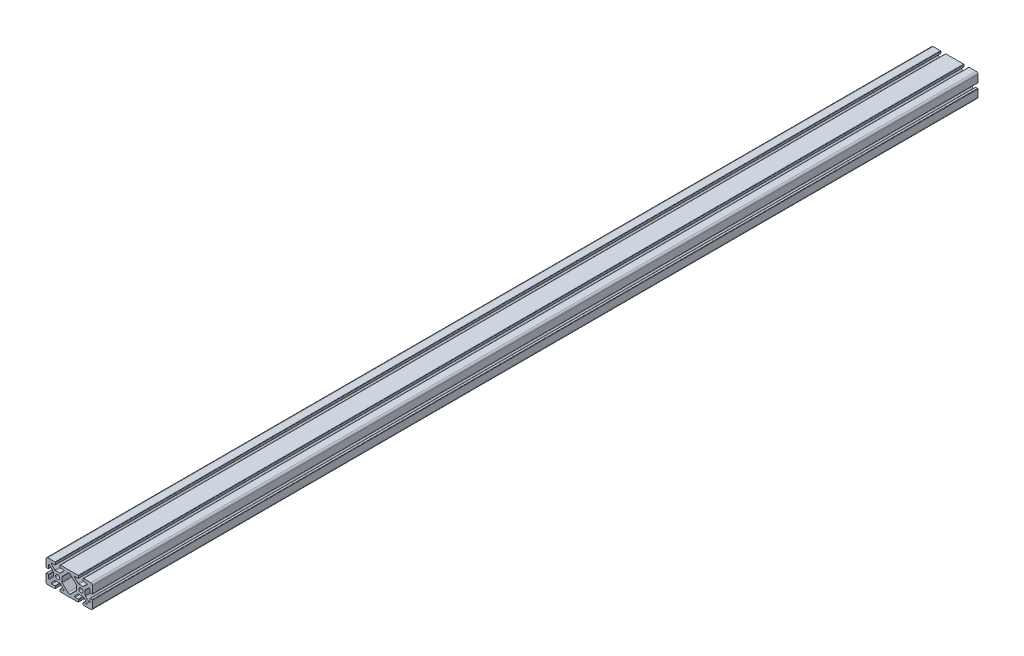
SolidWorks part; units mm, degrees
ref_plane "Front Plane" through (0, 0, 0) normal (0, 0, 1) x (1, 0, 0)
ref_plane "Top Plane" through (0, 0, 0) normal (0, 1, 0) x (1, 0, 0)
ref_plane "Right Plane" through (0, 0, 0) normal (1, 0, 0) x (0, 0, -1)
sketch "Sketch1" plane through (0, 0, 0) normal (0, 0, 1) x (1, 0, 0)
  line L0 (-40, 17) -> (-40, 4.75)
  line L1 (-37, 20) -> (-24.75, 20)
  line L2 (-24, 19.25) -> (-24, 16.25)
  line L3 (-24.75, 15.5) -> (-30.068, 15.5)
  line L4 (-30.727, 13.909) -> (-24.8599, 8.0419)
  line L5 (-33.909, 10.727) -> (-28.0419, 4.8599)
  line L6 (-35.5, 10.068) -> (-35.5, 4.75)
  line L7 (-36.25, 4) -> (-39.25, 4)
  line L8 (-23.5517, 7.5) -> (-16.4483, 7.5)
  line L9 (-27.5, 3.5517) -> (-27.5, -3.5517)
  line L10 (0, 20) -> (-15.25, 20)
  line L11 (-16, 19.25) -> (-16, 16.25)
  line L12 (-15.25, 15.5) -> (-9.932, 15.5)
  line L13 (-12.5, 3.5517) -> (-12.5, -3.5517)
  line L14 (-9.273, 13.909) -> (-15.1401, 8.0419)
  line L15 (-2.25, 14.568) -> (-11.9581, 4.8599)
  line L16 (-36.25, -4) -> (-39.25, -4)
  line L17 (-35.5, -10.068) -> (-35.5, -4.75)
  line L18 (-33.909, -10.727) -> (-28.0419, -4.8599)
  line L19 (-30.727, -13.909) -> (-24.8599, -8.0419)
  line L20 (-24.75, -15.5) -> (-30.068, -15.5)
  line L21 (-24, -19.25) -> (-24, -16.25)
  line L22 (-37, -20) -> (-24.75, -20)
  line L23 (-40, -17) -> (-40, -4.75)
  line L24 (0, -20) -> (-15.25, -20)
  line L25 (-16, -19.25) -> (-16, -16.25)
  line L26 (-15.25, -15.5) -> (-9.932, -15.5)
  line L27 (-9.273, -13.909) -> (-15.1401, -8.0419)
  line L28 (-2.25, -14.568) -> (-11.9581, -4.8599)
  line L29 (-23.5517, -7.5) -> (-16.4483, -7.5)
  line L58 (0, 20) -> (0, -20) construction
  line L59 (-12.5, 0) -> (0, 0) construction
  line L60 (0, 15.5) -> (15.25, 15.5) construction
  line L61 (0, -15.5) -> (15.25, -15.5) construction
  line L62 (-24, 17.75) -> (-16, 17.75) construction
  line L63 (-20, 17.75) -> (-20, 0) construction
  line L64 (-37.75, 4) -> (-37.75, -4) construction
  circle A0 centre (-20, 0) radius 3.5
  arc A1 (-40, 17) -> (-37, 20) centre (-37, 17) cw
  arc A2 (-33.909, 10.727) -> (-35.5, 10.068) centre (-34.568, 10.068) ccw
  arc A3 (-30.068, 15.5) -> (-30.727, 13.909) centre (-30.068, 14.568) ccw
  arc A4 (-24.75, 20) -> (-24, 19.25) centre (-24.75, 19.25) cw
  arc A5 (-40, 4.75) -> (-39.25, 4) centre (-39.25, 4.75) ccw
  arc A6 (-35.5, 4.75) -> (-36.25, 4) centre (-36.25, 4.75) cw
  arc A7 (-24, 16.25) -> (-24.75, 15.5) centre (-24.75, 16.25) cw
  arc A8 (-23.5517, 7.5) -> (-24.8599, 8.0419) centre (-23.5517, 9.35) cw
  arc A9 (-27.5, 3.5517) -> (-28.0419, 4.8599) centre (-29.35, 3.5517) ccw
  arc A10 (0, 15.5) -> (-2.25, 14.568) centre (0, 12.318) ccw
  arc A11 (-2.25, -14.568) -> (0, -15.5) centre (0, -12.318) ccw
  arc A12 (-15.25, 20) -> (-16, 19.25) centre (-15.25, 19.25) ccw
  arc A13 (-16, 16.25) -> (-15.25, 15.5) centre (-15.25, 16.25) ccw
  arc A14 (-16.4483, 7.5) -> (-15.1401, 8.0419) centre (-16.4483, 9.35) ccw
  arc A15 (-12.5, 3.5517) -> (-11.9581, 4.8599) centre (-10.65, 3.5517) cw
  arc A16 (-9.932, 15.5) -> (-9.273, 13.909) centre (-9.932, 14.568) cw
  arc A17 (-27.5, -3.5517) -> (-28.0419, -4.8599) centre (-29.35, -3.5517) cw
  arc A18 (-23.5517, -7.5) -> (-24.8599, -8.0419) centre (-23.5517, -9.35) ccw
  arc A19 (-24, -16.25) -> (-24.75, -15.5) centre (-24.75, -16.25) ccw
  arc A20 (-35.5, -4.75) -> (-36.25, -4) centre (-36.25, -4.75) ccw
  arc A21 (-40, -4.75) -> (-39.25, -4) centre (-39.25, -4.75) cw
  arc A22 (-24.75, -20) -> (-24, -19.25) centre (-24.75, -19.25) ccw
  arc A23 (-30.068, -15.5) -> (-30.727, -13.909) centre (-30.068, -14.568) cw
  arc A24 (-33.909, -10.727) -> (-35.5, -10.068) centre (-34.568, -10.068) cw
  arc A25 (-40, -17) -> (-37, -20) centre (-37, -17) ccw
  arc A26 (-9.932, -15.5) -> (-9.273, -13.909) centre (-9.932, -14.568) ccw
  arc A27 (-15.25, -20) -> (-16, -19.25) centre (-15.25, -19.25) cw
  arc A28 (-16, -16.25) -> (-15.25, -15.5) centre (-15.25, -16.25) cw
  arc A29 (-16.4483, -7.5) -> (-15.1401, -8.0419) centre (-16.4483, -9.35) cw
  arc A30 (-12.5, -3.5517) -> (-11.9581, -4.8599) centre (-10.65, -3.5517) ccw
  point P36 (-27.5, 0)
  point P98 (-37.75, 0)
  point P103 (-20, 7.5)
  point P105 (-20, -7.5)
  dimension "D7" = 7
  dimension "D9" = 3
  dimension "D17" = 0.75
  dimension "D23" = 1.85
  dimension "Rail Width" = 40
  dimension "Rail Height" = 80
  dimension "D3" = 40
  dimension "D4" = 20
  dimension "D6" = 4.5
  dimension "D8" = 4.5
  dimension "D10" = 4.5
  dimension "D11" = 4.5
  dimension "Slot Width" = 8
  dimension "D13" = 45
  dimension "D14" = 45
  dimension "D15" = 4.5
  dimension "D16" = 8
  dimension "D19" = 8
  dimension "D20" = 7.5
  dimension "D21" = 8
  dimension "D22" = 7.5
  dimension "D5" = 22
  dimension "D18" = 22
sketch "Sketch2" plane through (0, 0, 0) normal (1, 0, 0) x (0, 0, -1)
  line L0 (-762, -20) -> (762, -20)
  point P2 (-723.9, -20)
  point P3 (723.9, -20)
  dimension "Length" = 1524
  dimension "D1" = 38.1
  dimension "D2" = 38.1
sketch "Sketch3" plane through (0, 0, 0) normal (0, 0, 1) x (1, 0, 0)
  line L0 (0, 20) -> (-15.25, 20) construction
  line L1 (-16, 19.25) -> (-16, 16.25) construction
  line L2 (-15.25, 15.5) -> (-9.932, 15.5) construction
  line L3 (-9.273, 13.909) -> (-15.1401, 8.0419) construction
  line L4 (-23.5517, 7.5) -> (-16.4483, 7.5) construction
  line L5 (-30.727, 13.909) -> (-24.8599, 8.0419) construction
  line L6 (-24.75, 15.5) -> (-30.068, 15.5) construction
  line L7 (-24, 19.25) -> (-24, 16.25) construction
  line L8 (-37, 20) -> (-24.75, 20) construction
  line L9 (-40, 17) -> (-40, 4.75) construction
  line L10 (-36.25, 4) -> (-39.25, 4) construction
  line L11 (-35.5, 10.068) -> (-35.5, 4.75) construction
  line L12 (-33.909, 10.727) -> (-28.0419, 4.8599) construction
  line L13 (-27.5, 3.5517) -> (-27.5, -3.5517) construction
  line L14 (-33.909, -10.727) -> (-28.0419, -4.8599) construction
  line L15 (-35.5, -10.068) -> (-35.5, -4.75) construction
  line L16 (-36.25, -4) -> (-39.25, -4) construction
  line L17 (-40, -17) -> (-40, -4.75) construction
  line L18 (-37, -20) -> (-24.75, -20) construction
  line L19 (-24, -19.25) -> (-24, -16.25) construction
  line L20 (-24.75, -15.5) -> (-30.068, -15.5) construction
  line L21 (-30.727, -13.909) -> (-24.8599, -8.0419) construction
  line L22 (-23.5517, -7.5) -> (-16.4483, -7.5) construction
  line L23 (-9.273, -13.909) -> (-15.1401, -8.0419) construction
  line L24 (-15.25, -15.5) -> (-9.932, -15.5) construction
  line L25 (-16, -19.25) -> (-16, -16.25) construction
  line L26 (0, -20) -> (-15.25, -20) construction
  line L27 (-2.25, -14.568) -> (-11.9581, -4.8599) construction
  line L28 (-12.5, 3.5517) -> (-12.5, -3.5517) construction
  line L29 (-2.25, 14.568) -> (-11.9581, 4.8599) construction
  line L30 (15.25, 20) -> (-15.25, 20)
  line L31 (-16, 19.25) -> (-16, 16.25)
  line L32 (-15.25, 15.5) -> (-9.932, 15.5)
  line L33 (-9.273, 13.909) -> (-15.1401, 8.0419)
  line L34 (-23.5517, 7.5) -> (-16.4483, 7.5)
  line L35 (-30.727, 13.909) -> (-24.8599, 8.0419)
  line L36 (-24.75, 15.5) -> (-30.068, 15.5)
  line L37 (-24, 19.25) -> (-24, 16.25)
  line L38 (-37, 20) -> (-24.75, 20)
  line L39 (-40, 17) -> (-40, 4.75)
  line L40 (-36.25, 4) -> (-39.25, 4)
  line L41 (-35.5, 10.068) -> (-35.5, 4.75)
  line L42 (-33.909, 10.727) -> (-28.0419, 4.8599)
  line L43 (-27.5, 3.5517) -> (-27.5, -3.5517)
  line L44 (-33.909, -10.727) -> (-28.0419, -4.8599)
  line L45 (-35.5, -10.068) -> (-35.5, -4.75)
  line L46 (-36.25, -4) -> (-39.25, -4)
  line L47 (-40, -17) -> (-40, -4.75)
  line L48 (-37, -20) -> (-24.75, -20)
  line L49 (-24, -19.25) -> (-24, -16.25)
  line L50 (-24.75, -15.5) -> (-30.068, -15.5)
  line L51 (-30.727, -13.909) -> (-24.8599, -8.0419)
  line L52 (-23.5517, -7.5) -> (-16.4483, -7.5)
  line L53 (-9.273, -13.909) -> (-15.1401, -8.0419)
  line L54 (-15.25, -15.5) -> (-9.932, -15.5)
  line L55 (-16, -19.25) -> (-16, -16.25)
  line L56 (15.25, -20) -> (-15.25, -20)
  line L57 (-2.25, -14.568) -> (-11.9581, -4.8599)
  line L58 (-12.5, 3.5517) -> (-12.5, -3.5517)
  line L59 (-2.25, 14.568) -> (-11.9581, 4.8599)
  line L60 (0, 20) -> (0, -20) construction
  line L61 (2.25, 14.568) -> (11.9581, 4.8599)
  line L62 (12.5, 3.5517) -> (12.5, -3.5517)
  line L63 (2.25, -14.568) -> (11.9581, -4.8599)
  line L64 (16, 19.25) -> (16, 16.25)
  line L65 (15.25, 15.5) -> (9.932, 15.5)
  line L66 (9.273, 13.909) -> (15.1401, 8.0419)
  line L67 (23.5517, 7.5) -> (16.4483, 7.5)
  line L68 (30.727, 13.909) -> (24.8599, 8.0419)
  line L69 (24.75, 15.5) -> (30.068, 15.5)
  line L70 (24, 19.25) -> (24, 16.25)
  line L71 (37, 20) -> (24.75, 20)
  line L72 (40, 17) -> (40, 4.75)
  line L73 (36.25, 4) -> (39.25, 4)
  line L74 (35.5, 10.068) -> (35.5, 4.75)
  line L75 (33.909, 10.727) -> (28.0419, 4.8599)
  line L76 (27.5, 3.5517) -> (27.5, -3.5517)
  line L77 (33.909, -10.727) -> (28.0419, -4.8599)
  line L78 (35.5, -10.068) -> (35.5, -4.75)
  line L79 (36.25, -4) -> (39.25, -4)
  line L80 (40, -17) -> (40, -4.75)
  line L81 (37, -20) -> (24.75, -20)
  line L82 (24, -19.25) -> (24, -16.25)
  line L83 (24.75, -15.5) -> (30.068, -15.5)
  line L84 (30.727, -13.909) -> (24.8599, -8.0419)
  line L85 (23.5517, -7.5) -> (16.4483, -7.5)
  line L86 (9.273, -13.909) -> (15.1401, -8.0419)
  line L87 (15.25, -15.5) -> (9.932, -15.5)
  line L88 (16, -19.25) -> (16, -16.25)
  circle A0 centre (-20, 0) radius 3.5 construction
  arc A1 (-15.25, 20) -> (-16, 19.25) centre (-15.25, 19.25) ccw construction
  arc A2 (-16, 16.25) -> (-15.25, 15.5) centre (-15.25, 16.25) ccw construction
  arc A3 (-9.273, 13.909) -> (-9.932, 15.5) centre (-9.932, 14.568) ccw construction
  arc A4 (-16.4483, 7.5) -> (-15.1401, 8.0419) centre (-16.4483, 9.35) ccw construction
  arc A5 (-24.8599, 8.0419) -> (-23.5517, 7.5) centre (-23.5517, 9.35) ccw construction
  arc A6 (-30.068, 15.5) -> (-30.727, 13.909) centre (-30.068, 14.568) ccw construction
  arc A7 (-24.75, 15.5) -> (-24, 16.25) centre (-24.75, 16.25) ccw construction
  arc A8 (-24, 19.25) -> (-24.75, 20) centre (-24.75, 19.25) ccw construction
  arc A9 (-37, 20) -> (-40, 17) centre (-37, 17) ccw construction
  arc A10 (-40, 4.75) -> (-39.25, 4) centre (-39.25, 4.75) ccw construction
  arc A11 (-36.25, 4) -> (-35.5, 4.75) centre (-36.25, 4.75) ccw construction
  arc A12 (-33.909, 10.727) -> (-35.5, 10.068) centre (-34.568, 10.068) ccw construction
  arc A13 (-27.5, 3.5517) -> (-28.0419, 4.8599) centre (-29.35, 3.5517) ccw construction
  arc A14 (-28.0419, -4.8599) -> (-27.5, -3.5517) centre (-29.35, -3.5517) ccw construction
  arc A15 (-35.5, -10.068) -> (-33.909, -10.727) centre (-34.568, -10.068) ccw construction
  arc A16 (-35.5, -4.75) -> (-36.25, -4) centre (-36.25, -4.75) ccw construction
  arc A17 (-39.25, -4) -> (-40, -4.75) centre (-39.25, -4.75) ccw construction
  arc A18 (-40, -17) -> (-37, -20) centre (-37, -17) ccw construction
  arc A19 (-24.75, -20) -> (-24, -19.25) centre (-24.75, -19.25) ccw construction
  arc A20 (-24, -16.25) -> (-24.75, -15.5) centre (-24.75, -16.25) ccw construction
  arc A21 (-30.727, -13.909) -> (-30.068, -15.5) centre (-30.068, -14.568) ccw construction
  arc A22 (-23.5517, -7.5) -> (-24.8599, -8.0419) centre (-23.5517, -9.35) ccw construction
  arc A23 (-15.1401, -8.0419) -> (-16.4483, -7.5) centre (-16.4483, -9.35) ccw construction
  arc A24 (-9.932, -15.5) -> (-9.273, -13.909) centre (-9.932, -14.568) ccw construction
  arc A25 (-15.25, -15.5) -> (-16, -16.25) centre (-15.25, -16.25) ccw construction
  arc A26 (-16, -19.25) -> (-15.25, -20) centre (-15.25, -19.25) ccw construction
  arc A27 (-2.25, -14.568) -> (0, -15.5) centre (0, -12.318) ccw construction
  arc A28 (-12.5, -3.5517) -> (-11.9581, -4.8599) centre (-10.65, -3.5517) ccw construction
  arc A29 (-11.9581, 4.8599) -> (-12.5, 3.5517) centre (-10.65, 3.5517) ccw construction
  arc A30 (0, 15.5) -> (-2.25, 14.568) centre (0, 12.318) ccw construction
  circle A31 centre (-20, 0) radius 3.5
  arc A32 (-15.25, 20) -> (-16, 19.25) centre (-15.25, 19.25) ccw
  arc A33 (-16, 16.25) -> (-15.25, 15.5) centre (-15.25, 16.25) ccw
  arc A34 (-9.273, 13.909) -> (-9.932, 15.5) centre (-9.932, 14.568) ccw
  arc A35 (-16.4483, 7.5) -> (-15.1401, 8.0419) centre (-16.4483, 9.35) ccw
  arc A36 (-24.8599, 8.0419) -> (-23.5517, 7.5) centre (-23.5517, 9.35) ccw
  arc A37 (-30.068, 15.5) -> (-30.727, 13.909) centre (-30.068, 14.568) ccw
  arc A38 (-24.75, 15.5) -> (-24, 16.25) centre (-24.75, 16.25) ccw
  arc A39 (-24, 19.25) -> (-24.75, 20) centre (-24.75, 19.25) ccw
  arc A40 (-37, 20) -> (-40, 17) centre (-37, 17) ccw
  arc A41 (-40, 4.75) -> (-39.25, 4) centre (-39.25, 4.75) ccw
  arc A42 (-36.25, 4) -> (-35.5, 4.75) centre (-36.25, 4.75) ccw
  arc A43 (-33.909, 10.727) -> (-35.5, 10.068) centre (-34.568, 10.068) ccw
  arc A44 (-27.5, 3.5517) -> (-28.0419, 4.8599) centre (-29.35, 3.5517) ccw
  arc A45 (-28.0419, -4.8599) -> (-27.5, -3.5517) centre (-29.35, -3.5517) ccw
  arc A46 (-35.5, -10.068) -> (-33.909, -10.727) centre (-34.568, -10.068) ccw
  arc A47 (-35.5, -4.75) -> (-36.25, -4) centre (-36.25, -4.75) ccw
  arc A48 (-39.25, -4) -> (-40, -4.75) centre (-39.25, -4.75) ccw
  arc A49 (-40, -17) -> (-37, -20) centre (-37, -17) ccw
  arc A50 (-24.75, -20) -> (-24, -19.25) centre (-24.75, -19.25) ccw
  arc A51 (-24, -16.25) -> (-24.75, -15.5) centre (-24.75, -16.25) ccw
  arc A52 (-30.727, -13.909) -> (-30.068, -15.5) centre (-30.068, -14.568) ccw
  arc A53 (-23.5517, -7.5) -> (-24.8599, -8.0419) centre (-23.5517, -9.35) ccw
  arc A54 (-15.1401, -8.0419) -> (-16.4483, -7.5) centre (-16.4483, -9.35) ccw
  arc A55 (-9.932, -15.5) -> (-9.273, -13.909) centre (-9.932, -14.568) ccw
  arc A56 (-15.25, -15.5) -> (-16, -16.25) centre (-15.25, -16.25) ccw
  arc A57 (-16, -19.25) -> (-15.25, -20) centre (-15.25, -19.25) ccw
  arc A58 (-2.25, -14.568) -> (2.25, -14.568) centre (0, -12.318) ccw
  arc A59 (-12.5, -3.5517) -> (-11.9581, -4.8599) centre (-10.65, -3.5517) ccw
  arc A60 (-11.9581, 4.8599) -> (-12.5, 3.5517) centre (-10.65, 3.5517) ccw
  arc A61 (2.25, 14.568) -> (-2.25, 14.568) centre (0, 12.318) ccw
  circle A62 centre (20, 0) radius 3.5
  arc A63 (11.9581, 4.8599) -> (12.5, 3.5517) centre (10.65, 3.5517) cw
  arc A64 (12.5, -3.5517) -> (11.9581, -4.8599) centre (10.65, -3.5517) cw
  arc A65 (15.25, 20) -> (16, 19.25) centre (15.25, 19.25) cw
  arc A66 (16, 16.25) -> (15.25, 15.5) centre (15.25, 16.25) cw
  arc A67 (9.273, 13.909) -> (9.932, 15.5) centre (9.932, 14.568) cw
  arc A68 (16.4483, 7.5) -> (15.1401, 8.0419) centre (16.4483, 9.35) cw
  arc A69 (24.8599, 8.0419) -> (23.5517, 7.5) centre (23.5517, 9.35) cw
  arc A70 (30.068, 15.5) -> (30.727, 13.909) centre (30.068, 14.568) cw
  arc A71 (24.75, 15.5) -> (24, 16.25) centre (24.75, 16.25) cw
  arc A72 (24, 19.25) -> (24.75, 20) centre (24.75, 19.25) cw
  arc A73 (37, 20) -> (40, 17) centre (37, 17) cw
  arc A74 (40, 4.75) -> (39.25, 4) centre (39.25, 4.75) cw
  arc A75 (36.25, 4) -> (35.5, 4.75) centre (36.25, 4.75) cw
  arc A76 (33.909, 10.727) -> (35.5, 10.068) centre (34.568, 10.068) cw
  arc A77 (27.5, 3.5517) -> (28.0419, 4.8599) centre (29.35, 3.5517) cw
  arc A78 (28.0419, -4.8599) -> (27.5, -3.5517) centre (29.35, -3.5517) cw
  arc A79 (35.5, -10.068) -> (33.909, -10.727) centre (34.568, -10.068) cw
  arc A80 (35.5, -4.75) -> (36.25, -4) centre (36.25, -4.75) cw
  arc A81 (39.25, -4) -> (40, -4.75) centre (39.25, -4.75) cw
  arc A82 (40, -17) -> (37, -20) centre (37, -17) cw
  arc A83 (24.75, -20) -> (24, -19.25) centre (24.75, -19.25) cw
  arc A84 (24, -16.25) -> (24.75, -15.5) centre (24.75, -16.25) cw
  arc A85 (30.727, -13.909) -> (30.068, -15.5) centre (30.068, -14.568) cw
  arc A86 (23.5517, -7.5) -> (24.8599, -8.0419) centre (23.5517, -9.35) cw
  arc A87 (15.1401, -8.0419) -> (16.4483, -7.5) centre (16.4483, -9.35) cw
  arc A88 (9.932, -15.5) -> (9.273, -13.909) centre (9.932, -14.568) cw
  arc A89 (15.25, -15.5) -> (16, -16.25) centre (15.25, -16.25) cw
  arc A90 (16, -19.25) -> (15.25, -20) centre (15.25, -19.25) cw
extrude "Boss-Extrude1" add sketch "Sketch3" along normal mid plane 1524
equation "\"D10@Sketch1\"=\"D8@Sketch1\""
equation "\"D11@Sketch1\"=\"D10@Sketch1\""
equation "\"D15@Sketch1\"=\"D6@Sketch1\""
equation "\"D16@Sketch1\" = \"Slot Width@Sketch1\""
equation "\"D18@Sketch1\"=\"D5@Sketch1\""
equation "\"D1@Boss-Extrude1\"=\"Length@Sketch2\""
equation "\"D2@Sketch2\"=\"D1@Sketch2\""
